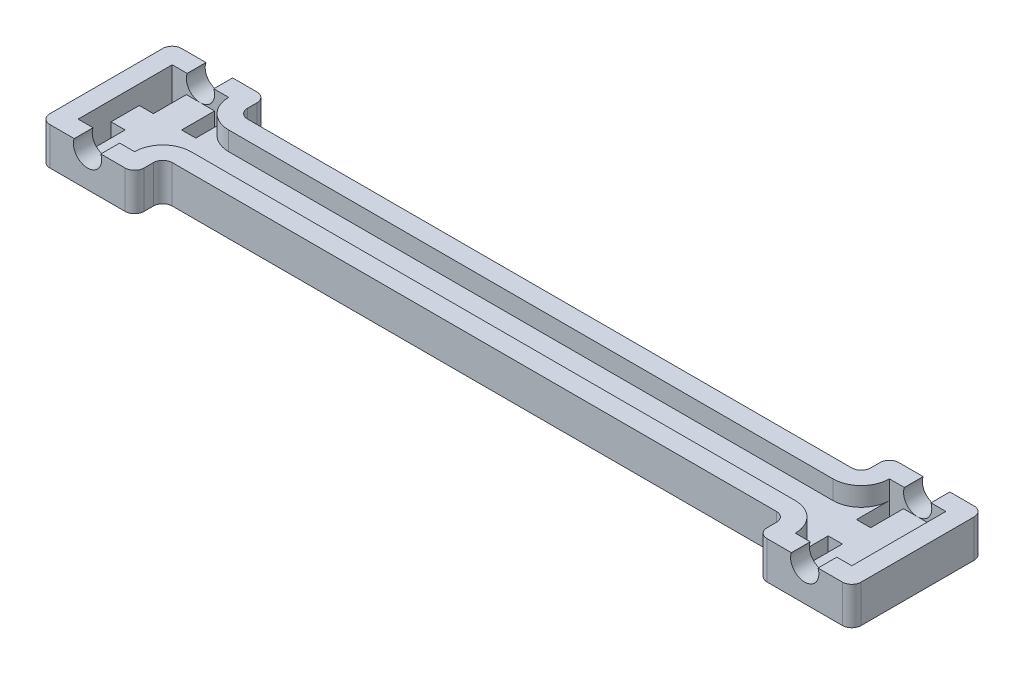
SolidWorks part; units mm, degrees
ref_plane "Front Plane" through (0, 0, 0) normal (0, 0, 1) x (1, 0, 0)
ref_plane "Top Plane" through (0, 0, 0) normal (0, 1, 0) x (1, 0, 0)
ref_plane "Right Plane" through (0, 0, 0) normal (1, 0, 0) x (0, 0, -1)
sketch "Sketch1" plane through (0, 0, 0) normal (0, 1, 0) x (1, 0, 0)
  line L0 (0, -4) -> (0, 4)
  line L1 (0, 4) -> (33.1, 4)
  line L2 (33.1, 4) -> (33.1, 7)
  line L3 (33.1, 7) -> (43.1, 7)
  line L4 (43.1, 7) -> (43.1, -7)
  line L5 (43.1, -7) -> (33.1, -7)
  line L6 (33.1, -7) -> (33.1, -4)
  line L7 (33.1, -4) -> (0, -4)
  line L8 (38.1, 7) -> (38.1, -8.1039) construction
  point P5 (0, 0)
  point P12 (0, 0)
  point P13 (38.1, 7)
  dimension "D1" = 8
  dimension "D2" = 38.1
  dimension "D3" = 10
  dimension "D4" = 14
extrude "Boss-Extrude1" add sketch "Sketch1" along normal blind 2
fillet "Fillet1" radius 1 6 edges at (33.1, 1, -4) (33.1, 1, -7) (43.1, 1, -7) (43.1, 1, 7) (33.1, 1, 7) (33.1, 1, 4)
sketch "Sketch2" plane through (0, 2, 0) normal (0, 1, 0) x (1, 0, 0)
  line L0 (38.1, 7) -> (38.1, -7) construction
  line L1 (42.1, 7) -> (34.1, 7) construction
  line L2 (34.1, -7) -> (42.1, -7) construction
  line L3 (35.1, -1.5) -> (35.1, -5)
  line L4 (39.6, 5) -> (41.1, 5)
  line L5 (39.6, 5) -> (39.6, 1.5)
  line L6 (39.6, 1.5) -> (41.1, 1.5)
  line L7 (41.1, 5) -> (41.1, 1.5)
  line L8 (39.6, -1.5) -> (41.1, -1.5)
  line L9 (39.6, -1.5) -> (39.6, -5)
  line L10 (39.6, -5) -> (41.1, -5)
  line L11 (41.1, -1.5) -> (41.1, -5)
  line L12 (36.6, -5) -> (35.1, -5)
  line L13 (36.6, -1.5) -> (36.6, -5)
  line L14 (36.6, -1.5) -> (35.1, -1.5)
  line L15 (35.1, 5) -> (35.1, 1.5)
  line L16 (36.6, 1.5) -> (35.1, 1.5)
  line L17 (36.6, 5) -> (36.6, 1.5)
  line L18 (36.6, 5) -> (35.1, 5)
  dimension "D1" = 2
  dimension "D2" = 3.5
  dimension "D3" = 2
  dimension "D4" = 3.5
  dimension "D5" = 1.5
  dimension "D6" = 1.5
extrude "Cut-Extrude1" cut sketch "Sketch2" against normal through all
sketch "Sketch5" plane through (0, 2, 0) normal (0, 1, 0) x (1, 0, 0)
  line L0 (0, -2) -> (32.1, -2)
  line L1 (35.1, -5) -> (35.1, -5)
  line L2 (35.1, -5) -> (41.1, -5)
  line L3 (41.1, -5) -> (41.1, 5)
  line L4 (41.1, 5) -> (35.1, 5)
  line L5 (35.1, 5) -> (35.1, 5)
  line L6 (32.1, 2) -> (0, 2)
  line L7 (0, 4) -> (0, 2)
  line L8 (42.1, 7) -> (34.1, 7)
  line L9 (33.1, 6) -> (33.1, 5)
  line L10 (32.1, 4) -> (0, 4)
  line L11 (0, 4) -> (0, -4)
  line L12 (0, -4) -> (32.1, -4)
  line L13 (33.1, -5) -> (33.1, -6)
  line L14 (34.1, -7) -> (42.1, -7)
  line L15 (43.1, -6) -> (43.1, 6)
  line L16 (42.1, 7) -> (34.1, 7)
  line L17 (33.1, 6) -> (33.1, 5)
  line L18 (32.1, 4) -> (0, 4)
  line L20 (0, -4) -> (32.1, -4)
  line L21 (33.1, -5) -> (33.1, -6)
  line L22 (34.1, -7) -> (42.1, -7)
  line L23 (43.1, -6) -> (43.1, 6)
  line L24 (0, -2) -> (0, -4)
  arc A0 (35.1, -5) -> (32.1, -2) centre (32.1, -5) ccw
  arc A1 (35.1, -5) -> (35.1, -5) centre (35.1, -5) ccw
  arc A2 (41.1, -5) -> (41.1, -5) centre (41.1, -5) ccw
  arc A3 (41.1, 5) -> (41.1, 5) centre (41.1, 5) ccw
  arc A4 (35.1, 5) -> (35.1, 5) centre (35.1, 5) ccw
  arc A5 (32.1, 2) -> (35.1, 5) centre (32.1, 5) ccw
  arc A6 (34.1, 7) -> (33.1, 6) centre (34.1, 6) ccw
  arc A7 (32.1, 4) -> (33.1, 5) centre (32.1, 5) ccw
  arc A8 (33.1, -5) -> (32.1, -4) centre (32.1, -5) ccw
  arc A9 (33.1, -6) -> (34.1, -7) centre (34.1, -6) ccw
  arc A10 (42.1, -7) -> (43.1, -6) centre (42.1, -6) ccw
  arc A11 (43.1, 6) -> (42.1, 7) centre (42.1, 6) ccw
  arc A12 (34.1, 7) -> (33.1, 6) centre (34.1, 6) ccw
  arc A13 (32.1, 4) -> (33.1, 5) centre (32.1, 5) ccw
  arc A14 (33.1, -5) -> (32.1, -4) centre (32.1, -5) ccw
  arc A15 (33.1, -6) -> (34.1, -7) centre (34.1, -6) ccw
  arc A16 (42.1, -7) -> (43.1, -6) centre (42.1, -6) ccw
  arc A17 (43.1, 6) -> (42.1, 7) centre (42.1, 6) ccw
  dimension "D1" = 0
  dimension "D2" = 2
extrude "Boss-Extrude2" add sketch "Sketch5" along normal blind 2
sketch "Sketch6" plane through (0, 0, 7) normal (0, 0, 1) x (1, 0, 0)
  circle A0 centre (38.1, 3.5) radius 1.5
  point P6 (0, 0)
  dimension "D1" = 3
extrude "Cut-Extrude2" cut sketch "Sketch6" along direction (0, 0, -1) on the side against the normal up to surface (14 mm away)
mirror "Mirror1" about plane through (0, 0, 0) normal (1, 0, 0) of "Cut-Extrude2", "Boss-Extrude2", "Cut-Extrude1", "Fillet1", "Boss-Extrude1"
